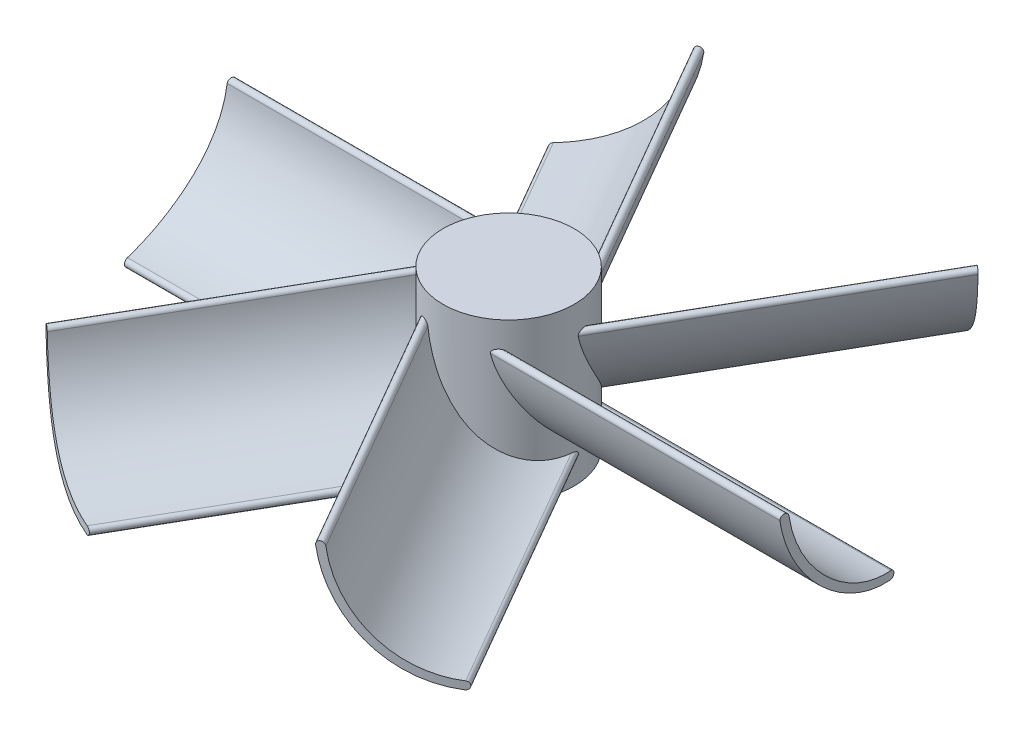
SolidWorks part; units mm, degrees
ref_plane "Ön Düzlem" through (0, 0, 0) normal (0, 0, 1) x (1, 0, 0)
ref_plane "Üst Düzlem" through (0, 0, 0) normal (0, 1, 0) x (1, 0, 0)
ref_plane "Sağ Düzlem" through (0, 0, 0) normal (1, 0, 0) x (0, 0, -1)
sketch "Çizim1" plane through (0, 0, 0) normal (0, 1, 0) x (1, 0, 0)
  circle A0 centre (0, 0) radius 12.5 construction
  circle A1 centre (0, -1.2156) radius 25
  dimension "D1" = 25
  dimension "D2" = 50
extrude "Yükseklik-Ekstrüzyon1" add sketch "Çizim1" along normal blind 60
ref_plane "Düzlem1" through (130, 0, 0) normal (1, 0, 0) x (0, 0, -1)
sketch "Çizim2" plane through (130, 0, 0) normal (1, 0, 0) x (0, 0, -1)
  arc A0 (-19.0413, 48.9696) -> (19.8921, 11.3967) centre (23.5997, 54.1966) ccw
  arc A1 (-22.019, 48.6046) -> (19.6332, 8.4079) centre (23.5997, 54.1966) ccw
  arc A2 (-22.019, 48.6046) -> (-19.0413, 48.9696) centre (-20.5301, 48.7871) cw
  arc A3 (19.6332, 8.4079) -> (19.8921, 11.3967) centre (19.7627, 9.9023) ccw
extrude "Yükseklik-Ekstrüzyon2" add sketch "Çizim2" against normal blind 120
pattern_circular "Dairesel Kaplama1" count 6 over 360 about axis through (0, 0, 1.2156) along (0, 1, 0) of "Yükseklik-Ekstrüzyon2"
sketch "Çizim4" plane through (0, 60, 0) normal (0, 1, 0) x (1, 0, 0)
  circle A0 centre (0, 0) radius 126.1695
extrude "Kes-Ekstrüzyon1" cut sketch "Çizim4" against normal blind 120 flip side to cut
